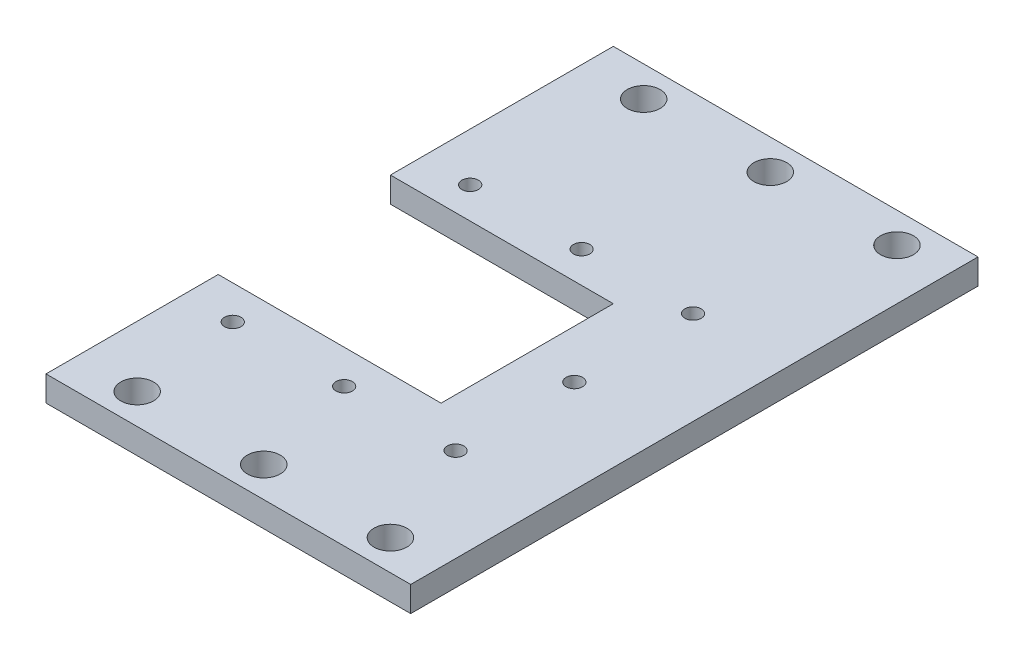
SolidWorks part; units mm, degrees
ref_plane "Front Plane" through (0, 0, 0) normal (0, 0, 1) x (1, 0, 0)
ref_plane "Top Plane" through (0, 0, 0) normal (0, 1, 0) x (1, 0, 0)
ref_plane "Right Plane" through (0, 0, 0) normal (1, 0, 0) x (0, 0, -1)
sketch "Sketch1" plane through (0, 0, 0) normal (0, 1, 0) x (1, 0, 0)
  line L1 (-57.15, -88.9) -> (57.15, -88.9)
  line L2 (-57.15, -88.9) -> (-57.15, 88.9)
  line L3 (-57.15, 88.9) -> (57.15, 88.9)
  line L4 (57.15, -88.9) -> (57.15, 88.9)
  line L5 (-57.15, -88.9) -> (57.15, 88.9) construction
  line L6 (-57.15, 88.9) -> (57.15, -88.9) construction
  point P0 (0, 0)
  dimension "D1" = 57.15
  dimension "D2" = 88.9
extrude "Boss-Extrude1" add sketch "Sketch1" along normal mid plane 7.9248
sketch "Sketch2" plane through (0, 0, 0) normal (0, 1, 0) x (1, 0, 0)
  line L1 (-171.45, -34.925) -> (12.7, -34.925)
  line L2 (-171.45, -34.925) -> (-171.45, 19.05)
  line L3 (-171.45, 19.05) -> (12.7, 19.05)
  line L4 (12.7, -34.925) -> (12.7, 19.05)
  point P8 (0, 0)
  dimension "D1" = 184.15
  dimension "D2" = 53.975
  dimension "D3" = 12.7
  dimension "D4" = 19.05
extrude "Cut-Extrude2" cut sketch "Sketch2" against normal through all from offset 3.9624
sketch "Sketch3" plane through (0, 0, 0) normal (0, 1, 0) x (1, 0, 0)
  circle A0 centre (-38.1, -79.375) radius 5.1562
  circle A1 centre (-38.1, 79.375) radius 5.1562
  point P4 (0, 0)
  dimension "D1" = 10.3124
  dimension "D2" = 10.3124
  dimension "D3" = 158.75
  dimension "D4" = 38.1
  dimension "D5" = 79.375
extrude "Cut-Extrude4" cut sketch "Sketch3" against normal through all from offset 3.9624
sketch "Sketch4" plane through (0, 0, 0) normal (0, 1, 0) x (1, 0, 0)
  circle A0 centre (1.5748, -79.375) radius 5.1562
  circle A1 centre (1.5748, 79.375) radius 5.1562
  point P4 (0, 0)
  dimension "D1" = 10.3124
  dimension "D2" = 10.3124
  dimension "D3" = 158.75
  dimension "D4" = 1.5748
  dimension "D5" = 79.375
extrude "Cut-Extrude6" cut sketch "Sketch4" against normal through all from offset 3.9624
sketch "Sketch5" plane through (0, 0, 0) normal (0, 1, 0) x (1, 0, 0)
  circle A0 centre (41.275, -79.375) radius 5.1562
  circle A1 centre (41.275, 79.375) radius 5.1562
  point P4 (0, 0)
  dimension "D1" = 10.3124
  dimension "D2" = 10.3124
  dimension "D3" = 158.75
  dimension "D4" = 41.275
  dimension "D5" = 79.375
extrude "Cut-Extrude8" cut sketch "Sketch5" against normal through all from offset 3.9624
sketch "Sketch6" plane through (0, 0, 0) normal (0, 1, 0) x (1, 0, 0)
  circle A0 centre (-41.9862, -45.5422) radius 2.5781
  circle A1 centre (-7.0612, -45.5422) radius 2.5781
  circle A2 centre (27.8638, -45.5422) radius 2.5781
  circle A3 centre (-41.9862, 28.8798) radius 2.5781
  circle A4 centre (-7.0612, 28.8798) radius 2.5781
  circle A5 centre (27.8638, 28.8798) radius 2.5781
  point P12 (0, 0)
  dimension "D1" = 5.1562
  dimension "D2" = 5.1562
  dimension "D3" = 5.1562
  dimension "D4" = 5.1562
  dimension "D5" = 5.1562
  dimension "D6" = 5.1562
  dimension "D7" = 34.925
  dimension "D8" = 69.85
  dimension "D9" = 74.422
  dimension "D10" = 27.8638
  dimension "D11" = 45.5422
extrude "Cut-Extrude10" cut sketch "Sketch6" against normal blind 114.3 from offset 3.9624
sketch "Sketch7" plane through (0, 0, 0) normal (0, 1, 0) x (1, 0, 0)
  circle A0 centre (27.8638, -8.3312) radius 2.5781
  point P2 (0, 0)
  dimension "D1" = 5.1562
  dimension "D2" = 27.8638
  dimension "D3" = 8.3312
extrude "Cut-Extrude12" cut sketch "Sketch7" against normal blind 114.3 from offset 3.9624
